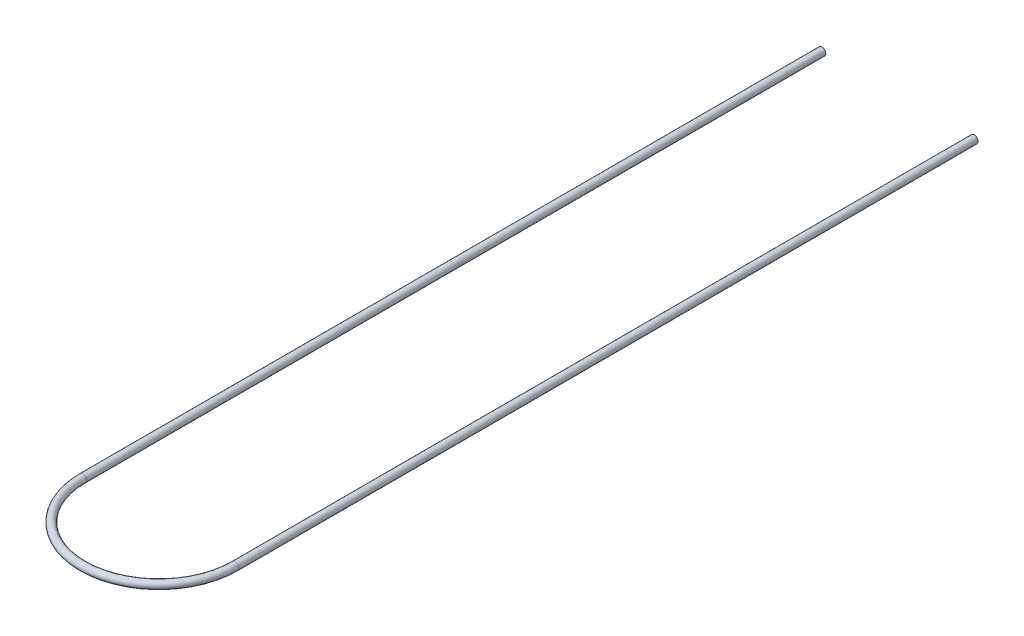
SolidWorks part; units mm, degrees
ref_plane "Front Plane" through (0, 0, 0) normal (0, 0, 1) x (1, 0, 0)
ref_plane "Top Plane" through (0, 0, 0) normal (0, 1, 0) x (1, 0, 0)
ref_plane "Right Plane" through (0, 0, 0) normal (1, 0, 0) x (0, 0, -1)
sketch "Sketch1" plane through (0, 0, 0) normal (0, 1, 0) x (1, 0, 0)
  line L0 (400.62, -300) -> (400.62, -2440)
  line L2 (-40, -300) -> (-40, -2440)
  arc A0 (-40, -2440) -> (400.62, -2440) centre (180.31, -2440) ccw
  dimension "D1" = 2140
  dimension "D2" = 440.62
ref_plane "Plane1" through (400.62, 0, 300) normal (0, 0, -1) x (-1, 0, 0)
sketch "Sketch2" plane through (400.62, 0, 300) normal (0, 0, -1) x (-1, 0, 0)
  circle A0 centre (0, 0) radius 9.95
  circle A1 centre (0, 0) radius 11.1
  dimension "D1" = 22.2
  dimension "D2" = 19.9
sweep "Sweep1" add profiles "Sketch2" path "Sketch1"
